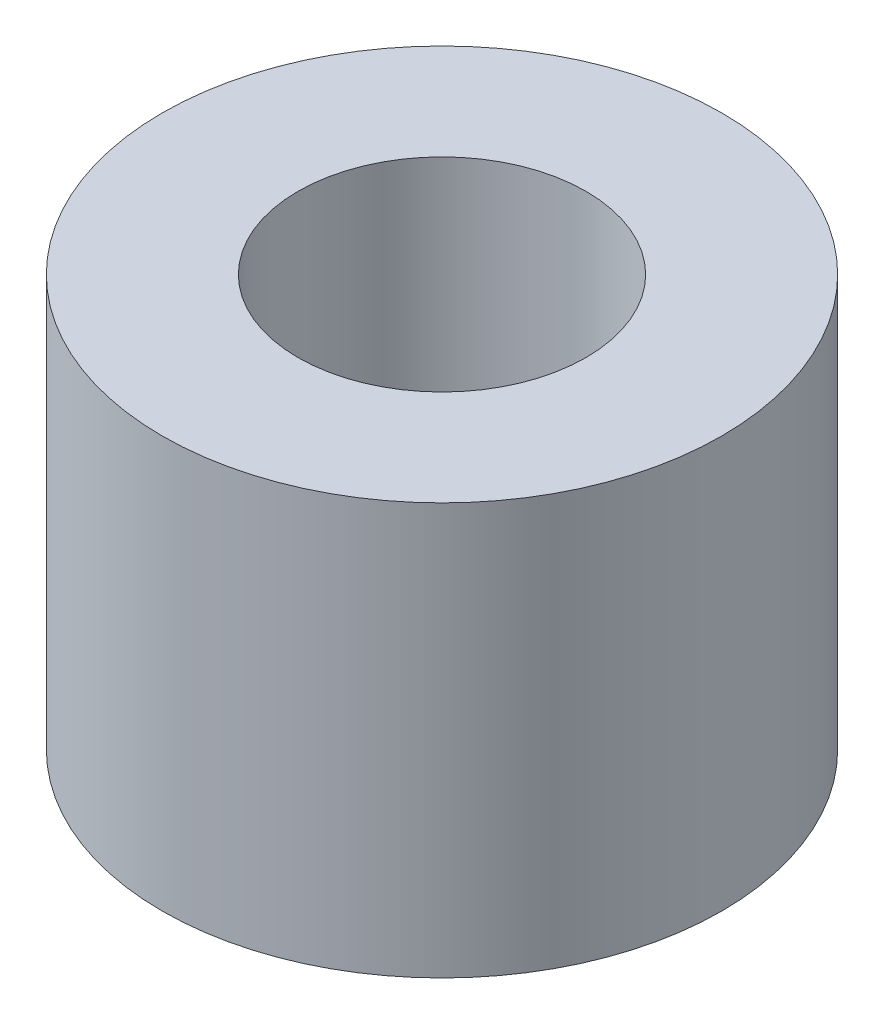
SolidWorks part; units mm, degrees
ref_plane "Front Plane" through (0, 0, 0) normal (0, 0, 1) x (1, 0, 0)
ref_plane "Top Plane" through (0, 0, 0) normal (0, 1, 0) x (1, 0, 0)
ref_plane "Right Plane" through (0, 0, 0) normal (1, 0, 0) x (0, 0, -1)
sketch "Sketch1" plane through (0, 0, 0) normal (0, 1, 0) x (1, 0, 0)
  circle A0 centre (0, 0) radius 3.4
  circle A1 centre (0, 0) radius 1.75
  dimension "D1" = 6.8
  dimension "D2" = 3.5
extrude "Boss-Extrude1" add sketch "Sketch1" along normal blind 5
